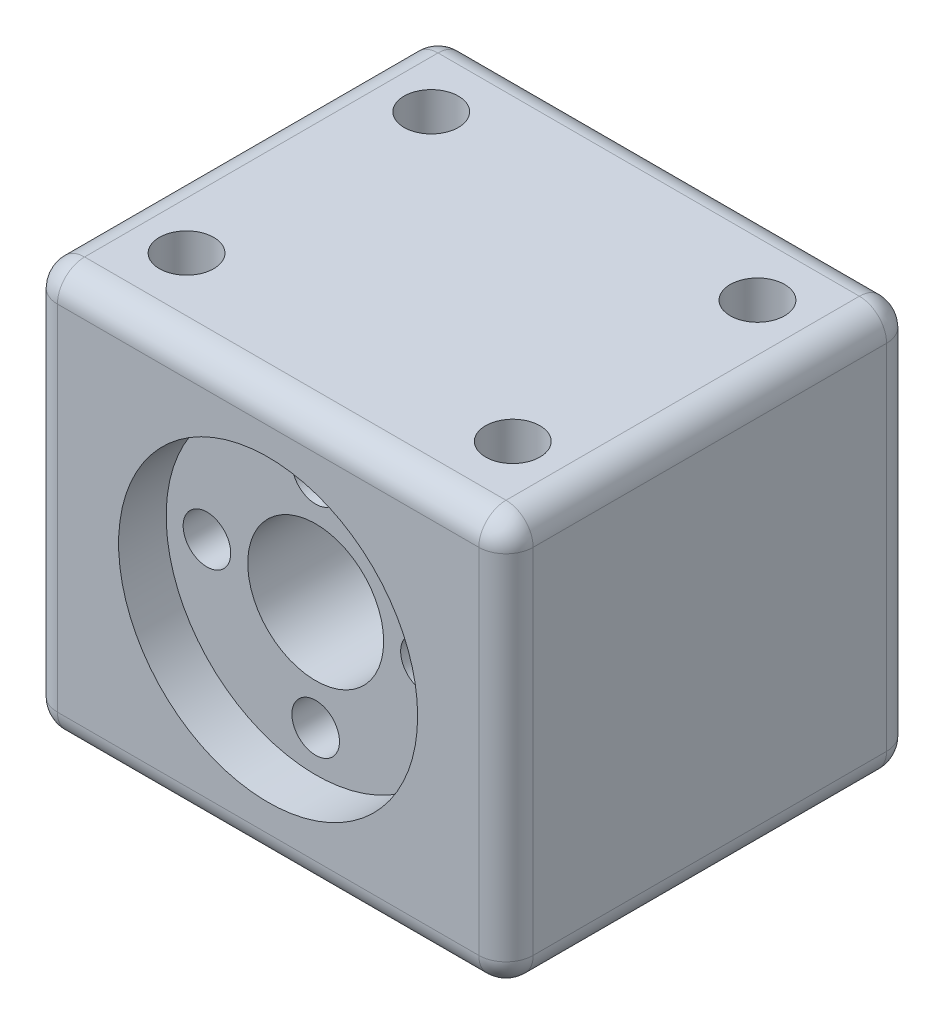
SolidWorks part; units mm, degrees
ref_plane "Alzado" through (0, 0, 0) normal (0, 0, 1) x (1, 0, 0)
ref_plane "Planta" through (0, 0, 0) normal (0, 1, 0) x (1, 0, 0)
ref_plane "Vista lateral" through (0, 0, 0) normal (1, 0, 0) x (0, 0, -1)
sketch "Croquis1" plane through (0, 0, 0) normal (0, 0, 1) x (1, 0, 0)
  line L1 (-17.5, -15) -> (17.5, -15)
  line L2 (-17.5, -15) -> (-17.5, 15)
  line L3 (-17.5, 15) -> (17.5, 15)
  line L4 (17.5, -15) -> (17.5, 15)
  line L5 (-17.5, -15) -> (17.5, 15) construction
  line L6 (-17.5, 15) -> (17.5, -15) construction
  circle A0 centre (0, 0) radius 5
  circle A1 centre (0, 0) radius 8 construction
  circle A2 centre (0, 0) radius 11 construction
  circle A3 centre (0, 8) radius 1.75
  circle A4 centre (8, 0) radius 1.75
  circle A5 centre (0, -8) radius 1.75
  circle A6 centre (-8, 0) radius 1.75
  point P20 (0, 0)
  dimension "D1" = 10
  dimension "D2" = 22
  dimension "D5" = 16
  dimension "D6" = 3.5
  dimension "D3" = 35
  dimension "D4" = 30
  dimension "D7" = 4
extrude "Saliente-Extruir1" add sketch "Croquis1" along normal blind 30
sketch "Croquis2" plane through (0, 0, 30) normal (0, 0, 1) x (1, 0, 0)
  circle A0 centre (0, 0) radius 11
  dimension "D1" = 22
extrude "Cortar-Extruir1" cut sketch "Croquis2" against normal blind 3.5
fillet "Redondeo2" radius 2 12 edges at (0, -15, 0) (17.5, 0, 0) (-17.5, 0, 0) (17.5, 0, 30) (0, 15, 0) (0, 15, 30) (0, -15, 30) (-17.5, 0, 30) (-17.5, 15, 15) (17.5, 15, 15) (17.5, -15, 15) (-17.5, -15, 15)
sketch "Croquis3" plane through (0, 15, 0) normal (0, 1, 0) x (1, 0, 0)
  line L0 (-15.5, -15) -> (15.5, -15) construction
  line L1 (-15.5, -2) -> (15.5, -2) construction
  line L2 (-15.5, -2) -> (-15.5, -28) construction
  line L3 (-15.5, -28) -> (15.5, -28) construction
  line L4 (15.5, -2) -> (15.5, -28) construction
  line L5 (12, -6) -> (-12, -24) construction
  circle A0 centre (-12, -24) radius 2
  circle A1 centre (12, -24) radius 2
  circle A2 centre (-12, -6) radius 2
  circle A3 centre (12, -6) radius 2
  point P14 (0, -15)
  point P15 (0, -15)
  dimension "D1" = 4
  dimension "D2" = 4
  dimension "D3" = 4
  dimension "D4" = 4
  dimension "D5" = 18
  dimension "D6" = 24
extrude "Cortar-Extruir2" cut sketch "Croquis3" against normal blind 31.5 and the other way blind 10
